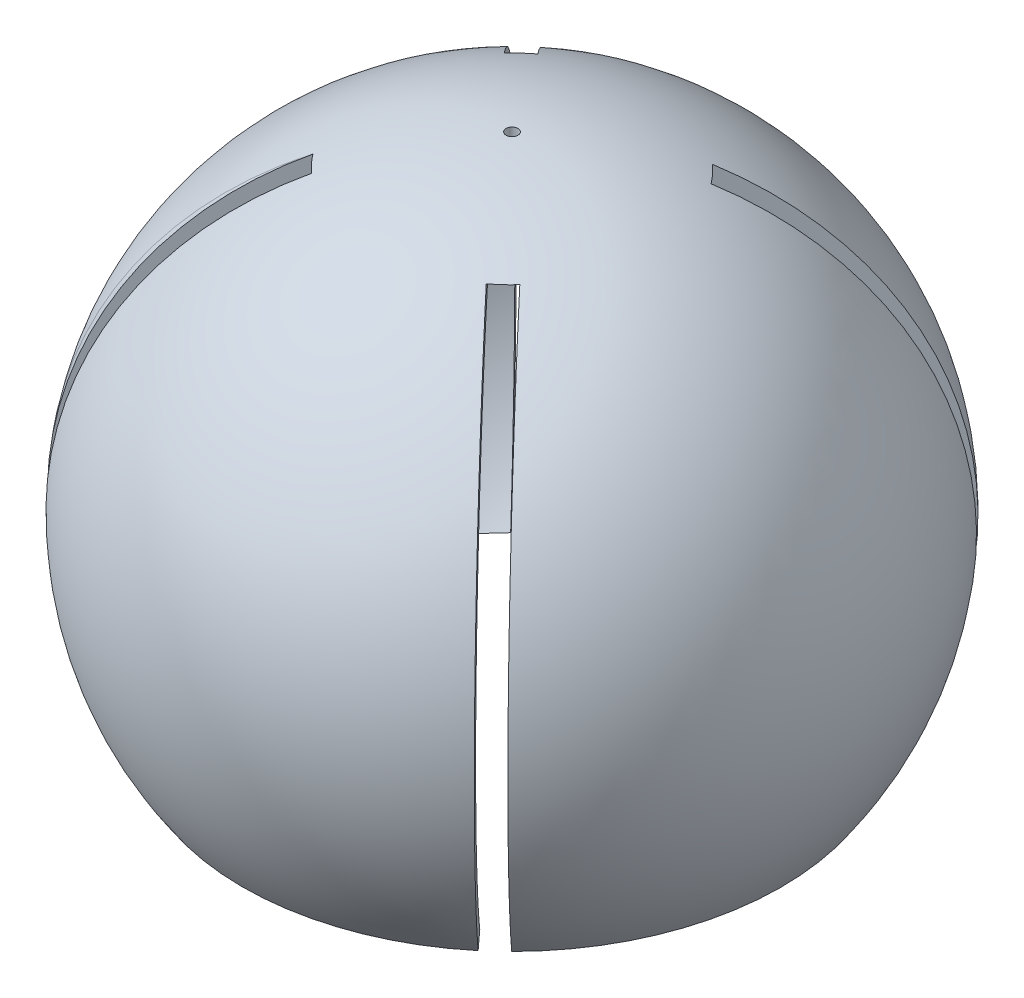
SolidWorks part; units mm, degrees
ref_plane "Front Plane" through (0, 0, 0) normal (0, 0, 1) x (1, 0, 0)
ref_plane "Top Plane" through (0, 0, 0) normal (0, 1, 0) x (1, 0, 0)
ref_plane "Right Plane" through (0, 0, 0) normal (1, 0, 0) x (0, 0, -1)
sketch "Sketch1" plane through (0, 0, 0) normal (0, 0, 1) x (1, 0, 0)
  line L0 (0, 27.7044) -> (0, -27.7513) construction
  line L1 (0, 27.7044) -> (0, -27.7513)
  arc A0 (0, 27.7044) -> (0, -27.7513) centre (0, -0.0235) ccw
  dimension "D1" = 27.7278
revolve "Revolve1" add sketch "Sketch1" angle 360 about L0
sketch "Sketch3" plane through (0, 0, 0) normal (0, 1, 0) x (1, 0, 0)
  line L0 (-17.9563, 21.1282) -> (0.0635, 1.4128)
  line L1 (0.0635, 1.4128) -> (19.7789, 19.4326)
  line L2 (-19.4326, 19.7789) -> (-1.4128, 0.0635)
  line L3 (-1.4128, 0.0635) -> (-21.1282, -17.9563)
  line L4 (-19.7789, -19.4326) -> (-0.0635, -1.4128)
  line L5 (-0.0635, -1.4128) -> (17.9563, -21.1282)
  line L6 (19.4326, -19.7789) -> (1.4128, -0.0635)
  line L7 (1.4128, -0.0635) -> (21.1282, 17.9563)
  circle A0 centre (0, 0) radius 27.7278 construction
  arc A1 (-19.4326, 19.7789) -> (-17.9563, 21.1282) centre (0, 0) cw
  arc A2 (21.1282, 17.9563) -> (19.7789, 19.4326) centre (0, 0) ccw
  arc A3 (19.4326, -19.7789) -> (17.9563, -21.1282) centre (0, 0) cw
  arc A4 (-21.1282, -17.9563) -> (-19.7789, -19.4326) centre (0, 0) ccw
  dimension "D1" = 1
extrude "Cut-Extrude1" cut sketch "Sketch3" against normal mid plane 50
sketch "Sketch5" plane through (0, 0, 0) normal (0, 0, 1) x (1, 0, 0)
  line L0 (0, -26) -> (0, 0)
  line L1 (0, 0) -> (0, 26)
  line L2 (0, 31.6306) -> (0, -32.8549) construction
  arc A0 (0, 26) -> (0, -26) centre (0, 0) ccw
  dimension "D1" = 26
revolve "Cut-Revolve1" cut sketch "Sketch5" angle 360 about L2
sketch "Sketch6" plane through (0, 0, 0) normal (0, 0, 1) x (1, 0, 0)
  line L2 (42.1149, -40.0764) -> (-38.794, -40.0764)
  line L4 (-38.794, -40.0764) -> (-38.794, -16)
  line L5 (-38.794, -16) -> (42.1149, -16)
  line L6 (42.1149, -16) -> (42.1149, -40.0764)
  dimension "D1" = 16
extrude "Cut-Extrude4" cut sketch "Sketch6" against normal mid plane 60
sketch "Sketch7" plane through (0, 0, 0) normal (0, 1, 0) x (1, 0, 0)
  circle A0 centre (0, 0) radius 0.5
  dimension "D1" = 1
extrude "Cut-Extrude5" cut sketch "Sketch7" against normal mid plane 60
